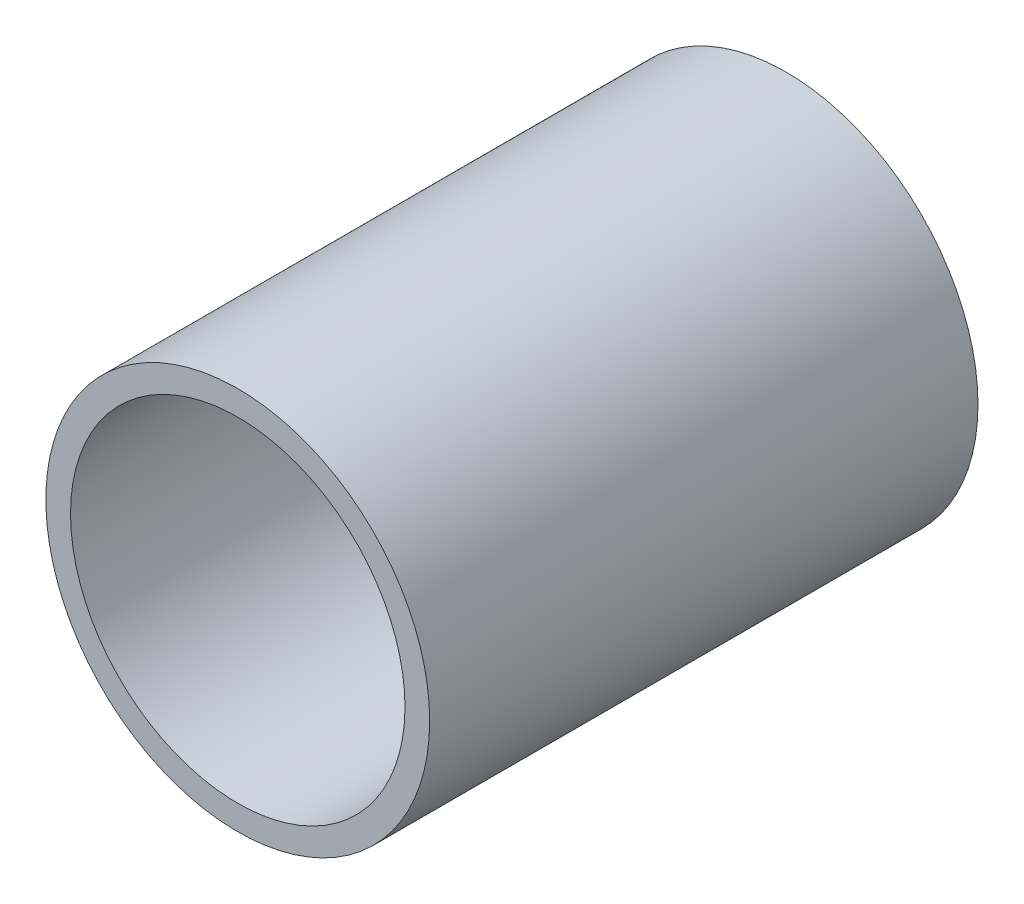
SolidWorks part; units mm, degrees
ref_plane "Front Plane" through (0, 0, 0) normal (0, 0, 1) x (1, 0, 0)
ref_plane "Top Plane" through (0, 0, 0) normal (0, 1, 0) x (1, 0, 0)
ref_plane "Right Plane" through (0, 0, 0) normal (1, 0, 0) x (0, 0, -1)
sketch "Sketch1" plane through (0, 0, 0) normal (0, 0, 1) x (1, 0, 0)
  line L0 (3.5, 0) -> (3.05, 0) construction
  line L1 (-3.5, 0) -> (3.5, 0) construction
  dimension "OD" = 7
  dimension "Wall Thickness" = 0.45
sketch "Sketch2" plane through (0, 0, 0) normal (1, 0, 0) x (0, 0, -1)
  line L0 (5, 0) -> (-5, 0)
  point P4 (0, 0)
  dimension "Length" = 10
sketch "Sketch3" plane through (0, 0, 0) normal (0, 0, 1) x (1, 0, 0)
  circle A0 centre (0, 0) radius 3.5
  circle A1 centre (0, 0) radius 3.05
extrude "Boss-Extrude1" add sketch "Sketch3" along normal up to vertex (5 mm away) and the other way up to vertex (5 mm away) up to point (0, 0, 5) other way up to point (0, 0, -5)
